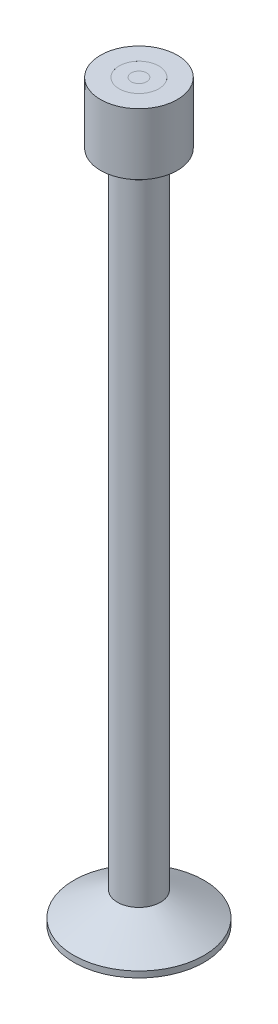
SolidWorks part; units mm, degrees
ref_plane "Alzado" through (0, 0, 0) normal (0, 0, 1) x (1, 0, 0)
ref_plane "Planta" through (0, 0, 0) normal (0, 1, 0) x (1, 0, 0)
ref_plane "Vista lateral" through (0, 0, 0) normal (1, 0, 0) x (0, 0, -1)
sketch "Croquis1" plane through (0, 0, 0) normal (0, 0, 1) x (1, 0, 0)
  line L0 (0, -22.5273) -> (0, 60.571) construction
  line L1 (5.375, 0) -> (5.375, 0.5)
  line L2 (5.375, 0.5) -> (1.78, 2.5)
  line L3 (1.78, 2.5) -> (1.78, 54.5)
  line L4 (1.78, 54.5) -> (3.1718, 55.5)
  line L5 (3.1718, 55.5) -> (3.1718, 60.571)
  line L6 (1.375, 54.9422) -> (1.375, 0)
  line L7 (1.375, 0) -> (5.375, 0)
  line L8 (0.375, 0.1) -> (0.375, 54.9422)
  line L9 (0.375, 54.9422) -> (0.635, 60.571)
  line L10 (0.375, 0.1) -> (0, 0.1)
  line L11 (0, 60.571) -> (0, 0.1)
  line L12 (0, 60.9797) -> (0, 62.2297) construction
  line L13 (3.1718, 60.571) -> (1.635, 60.571)
  line L14 (0.4604, 60.571) -> (-0.4604, 60.571) construction
  line L23 (1.375, 54.9422) -> (1.635, 60.571)
  line L26 (0.635, 60.571) -> (0.4424, 60.571)
  line L27 (0.4424, 60.571) -> (0, 60.571)
  dimension "D1" = 55
  dimension "D2" = 10.75
  dimension "D3" = 2
  dimension "D4" = 0.5
  dimension "D5" = 0.75
  dimension "D6" = 2.75
  dimension "D7" = 3.56
  dimension "D8" = 1
  dimension "D9" = 0.1
revolve "Revolución1" add sketch "Croquis1" angle 360 about L11
sketch "Croquis3" plane through (0, 0, 0) normal (0, 0, 1) x (1, 0, 0)
  line L0 (0, 55.5) -> (0, 0) construction
  line L1 (0.375, 54.9422) -> (0.635, 60.571)
  line L2 (0.635, 60.571) -> (-0.635, 60.571) construction
  line L3 (0.635, 60.571) -> (-0.635, 60.571) construction
  line L4 (0.635, 60.571) -> (1.635, 60.571)
  line L5 (1.375, 0.1) -> (0.375, 0.1)
  line L6 (0.635, 60.571) -> (0.4424, 60.571)
  line L7 (0.375, 0.1) -> (0.375, 54.9422)
  line L8 (0, 0.1) -> (0.375, 0.1)
  line L9 (0, 60.571) -> (0, 0.1)
  line L10 (0.375, 54.9422) -> (0.635, 60.571)
  line L12 (0.4424, 60.571) -> (0, 60.571)
  line L13 (0.375, 0.1) -> (0.375, 54.9422)
  line L20 (3.1718, 55.5) -> (3.1718, 60.571)
  line L21 (1.78, 54.5) -> (3.1718, 55.5)
  line L22 (1.78, 2.5) -> (1.78, 54.5)
  line L23 (5.375, 0.5) -> (1.78, 2.5)
  line L24 (5.375, 0) -> (5.375, 0.5)
  line L25 (1.375, 0) -> (5.375, 0)
  line L26 (1.375, 54.9422) -> (1.375, 0)
  line L27 (1.635, 60.571) -> (1.375, 54.9422)
  line L28 (1.635, 60.571) -> (1.375, 54.9422)
  line L29 (3.1718, 60.571) -> (1.635, 60.571)
  line L34 (1.375, 54.9422) -> (1.375, 0.1)
  dimension "D1" = 0
  dimension "D2" = 0
revolve "Revolución2" add sketch "Croquis3" angle 360 about L0
sketch "Croquis4" plane through (0, 0, 0) normal (0, -1, 0) x (1, 0, 0)
  circle A1 centre (0, 0) radius 1.375
  circle A2 centre (0, 0) radius 1.375
  dimension "D1" = 0
extrude "Saliente-Extruir1" add sketch "Croquis4" against normal up to surface (0.1 mm away) separate body up to face at (0, 0.1, 1.375)
